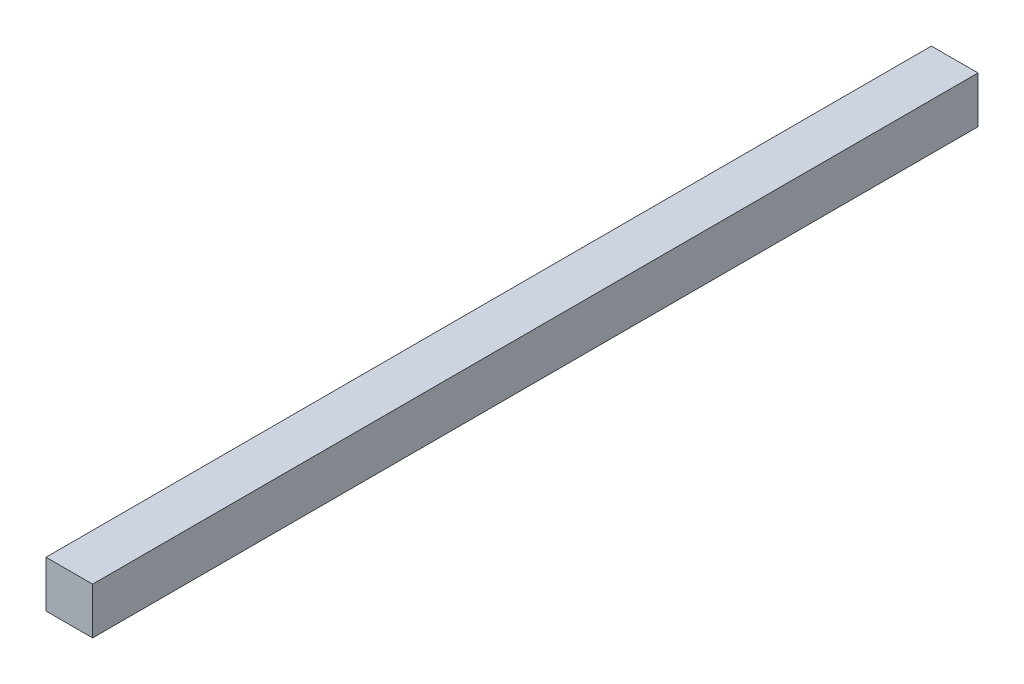
SolidWorks part; units mm, degrees
ref_plane "Front Plane" through (0, 0, 0) normal (0, 0, 1) x (1, 0, 0)
ref_plane "Top Plane" through (0, 0, 0) normal (0, 1, 0) x (1, 0, 0)
ref_plane "Right Plane" through (0, 0, 0) normal (1, 0, 0) x (0, 0, -1)
sketch "Sketch1" plane through (0, 0, 0) normal (0, 1, 0) x (1, 0, 0)
  line L1 (-12.7, 241.3) -> (12.7, 241.3)
  line L2 (-12.7, 241.3) -> (-12.7, -241.3)
  line L3 (-12.7, -241.3) -> (12.7, -241.3)
  line L4 (12.7, 241.3) -> (12.7, -241.3)
  line L5 (-12.7, 241.3) -> (12.7, -241.3) construction
  line L6 (-12.7, -241.3) -> (12.7, 241.3) construction
  point P0 (0, 0)
  dimension "D1" = 482.6
  dimension "D2" = 25.4
extrude "Boss-Extrude1" add sketch "Sketch1" along normal blind 25.4
